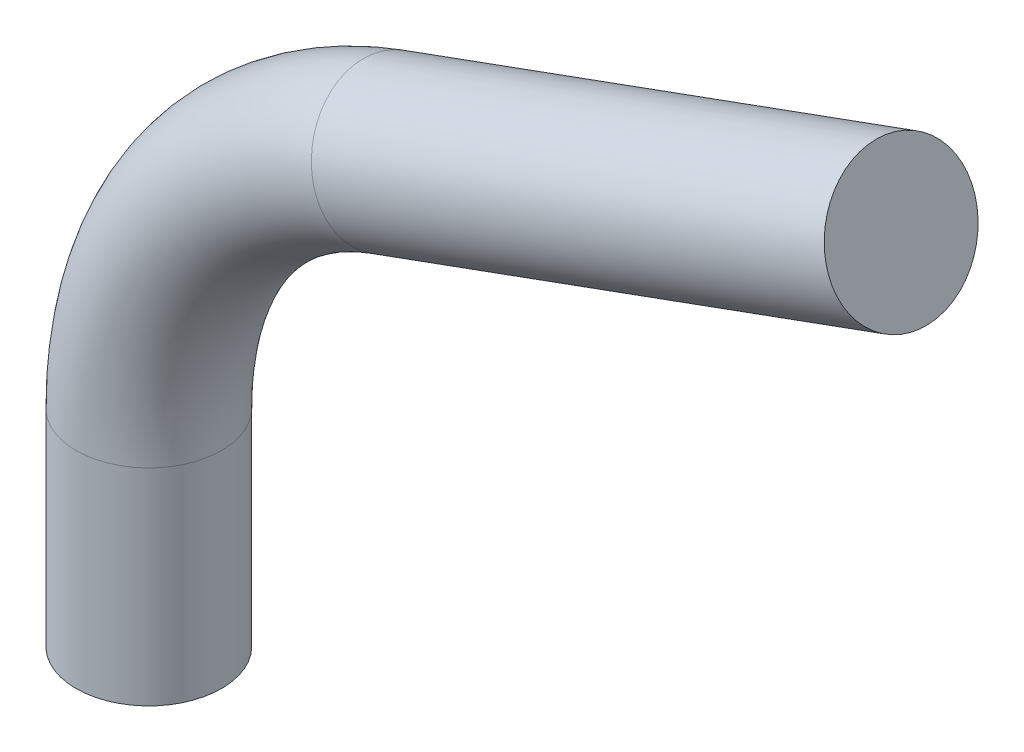
SolidWorks part; units mm, degrees
ref_plane "Front Plane" through (0, 0, 0) normal (0, 0, 1) x (1, 0, 0)
ref_plane "Top Plane" through (0, 0, 0) normal (0, 1, 0) x (1, 0, 0)
ref_plane "Right Plane" through (0, 0, 0) normal (1, 0, 0) x (0, 0, -1)
sketch "Sketch1" plane through (0, 0, 0) normal (0, 0, 1) x (1, 0, 0)
  line L0 (0, 0) -> (0, 8.4969)
  line L1 (9.8697, 22.5923) -> (31.0099, 30.2867)
  arc A0 (0, 8.4969) -> (9.8697, 22.5923) centre (15, 8.4969) cw
  point P6 (0, 19)
  dimension "D3" = 15
  dimension "D1" = 33
  dimension "D2" = 19
  dimension "D4" = 110
sketch "Sketch2" plane through (0, 0, 0) normal (0, 1, 0) x (1, 0, 0)
  circle A0 centre (0, 0) radius 3
  dimension "D1" = 6
sketch "Sketch3" plane through (0, 0, 0) normal (0, 0, 1) x (1, 0, 0)
  circle A0 centre (4, 0) radius 0.5
  dimension "D1" = 1
  dimension "D2" = 4
sweep "Sweep1" add profiles "Sketch2" path "Sketch1"
